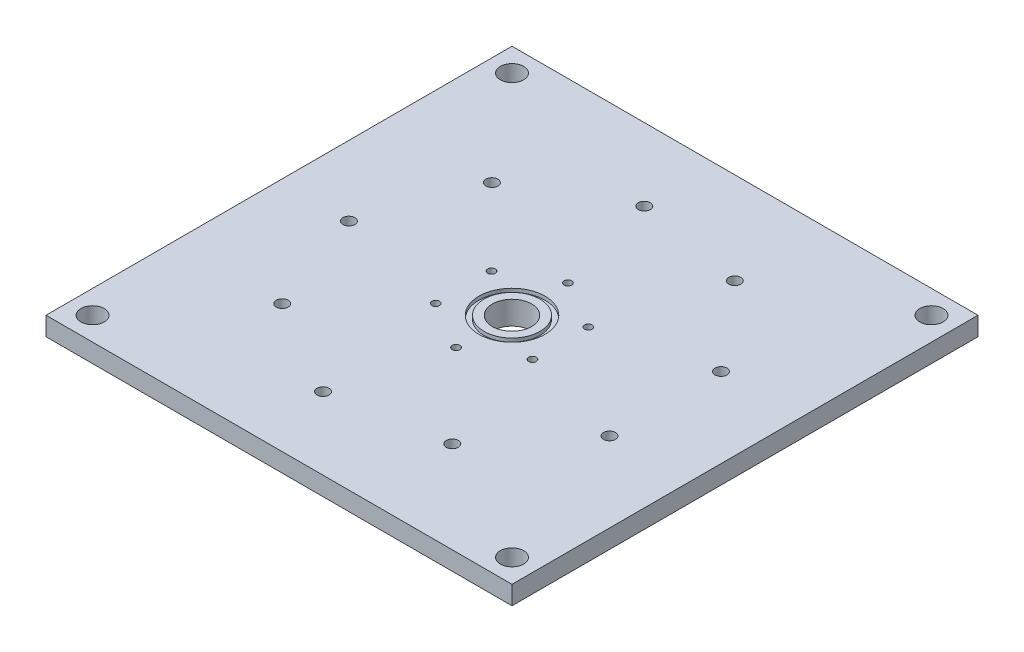
SolidWorks part; units mm, degrees
ref_plane "Front Plane" through (0, 0, 0) normal (0, 0, 1) x (1, 0, 0)
ref_plane "Top Plane" through (0, 0, 0) normal (0, 1, 0) x (1, 0, 0)
ref_plane "Right Plane" through (0, 0, 0) normal (1, 0, 0) x (0, 0, -1)
sketch "Sketch1" plane through (0, 0, 0) normal (0, 1, 0) x (1, 0, 0)
  line L1 (-63.5, -63.5) -> (63.5, -63.5)
  line L2 (-63.5, -63.5) -> (-63.5, 63.5)
  line L3 (-63.5, 63.5) -> (63.5, 63.5)
  line L4 (63.5, -63.5) -> (63.5, 63.5)
  line L5 (-63.5, -63.5) -> (63.5, 63.5) construction
  line L6 (-63.5, 63.5) -> (63.5, -63.5) construction
  point P0 (0, 0)
  dimension "D1" = 127
  dimension "D2" = 127
extrude "Boss-Extrude1" add sketch "Sketch1" along normal blind 5.08
sketch "Sketch2" plane through (0, 5.08, 0) normal (0, 1, 0) x (1, 0, 0)
  circle A0 centre (0, 0) radius 5.3467
extrude "Cut-Extrude1" cut sketch "Sketch2" against normal up to next
sketch "Sketch4" plane through (0, 5.08, 0) normal (0, 1, 0) x (1, 0, 0)
  circle A0 centre (0, 0) radius 7.62
  circle A1 centre (0, 0) radius 9.017
  dimension "D1" = 1.397
  dimension "D2" = 15.24
extrude "Cut-Extrude3" cut sketch "Sketch4" against normal blind 0.9779
sketch "Sketch5" plane through (0, 5.08, 0) normal (0, 1, 0) x (1, 0, 0)
  circle A0 centre (0, 0) radius 15.24 construction
  circle A1 centre (0, -15.24) radius 1.0325
  dimension "D1" = 2.065
extrude "Cut-Extrude4" cut sketch "Sketch5" against normal blind 3.175
pattern_circular "CirPattern1" count 6 over 360 about axis through (0, 0, 0) along (0, 1, 0) of "Cut-Extrude4"
sketch "Sketch6" plane through (0, 5.08, 0) normal (0, 1, 0) x (1, 0, 0)
  line L0 (0, 0) -> (22.225, -38.4948) construction
  circle A0 centre (0, 0) radius 44.45 construction
  circle A1 centre (22.225, -38.4948) radius 1.632
  dimension "D1" = 88.9
extrude "Cut-Extrude5" cut sketch "Sketch6" against normal up to next
pattern_circular "CirPattern2" count 9 over 360 about axis through (0, 0, 0) along (0, 1, 0) of "Cut-Extrude5"
sketch "Sketch7" plane through (0, 5.08, 0) normal (0, 1, 0) x (1, 0, 0)
  line L0 (63.5, 63.5) -> (-63.5, 63.5) construction
  line L1 (63.5, -63.5) -> (63.5, 63.5) construction
  line L2 (0, 0) -> (63.5, 0) construction
  line L3 (0, 0) -> (0, 63.5) construction
  circle A0 centre (57.15, 57.15) radius 3.175
  circle A1 centre (0, 0) radius 38.1 construction
  circle A2 centre (57.15, -57.15) radius 3.175
  circle A3 centre (-57.15, -57.15) radius 3.175
  circle A4 centre (-57.15, 57.15) radius 3.175
  circle A5 centre (57.15, 57.15) radius 5.5562 construction
  dimension "D1" = 6.35
  dimension "D2" = 6.35
extrude "Cut-Extrude6" cut sketch "Sketch7" against normal up to next
sketch "Sketch9" plane through (0, 0, 0) normal (0, -1, 0) x (1, 0, 0)
  circle A0 centre (0, 0) radius 10.9855
  circle A1 centre (0, 0) radius 5.3467
  dimension "D1" = 10.6934
  dimension "D2" = 21.971
extrude "Boss-Extrude2" add sketch "Sketch9" along normal blind 1.27
sketch "Sketch8" plane through (0, 5.08, 0) normal (0, 1, 0) x (1, 0, 0)
  line L0 (0, 0) -> (38.1, 0) construction
  circle A0 centre (38.1, 0) radius 0.7937
  dimension "D1" = 1.5875
  dimension "D2" = 38.1
extrude "Cut-Extrude7" [suppressed] cut sketch "Sketch8" against normal through all both and the other way through all
equation "\"AnnulusPlateThickness\"= 0.2"
equation "\"D1@Boss-Extrude1\"=\"AnnulusPlateThickness\""
equation "\"CenterRadius\"= 0.421 / 2"
equation "\"D1@Sketch2\"=\"CenterRadius\"*2"
equation "\"Basesidelength\"= 5"
equation "\"D2@Sketch1\"= \"Basesidelength\""
equation "\"D1@Sketch1\"= \"Basesidelength\""
equation "\"D1@Sketch9\"= \"CenterRadius\" * 2"
